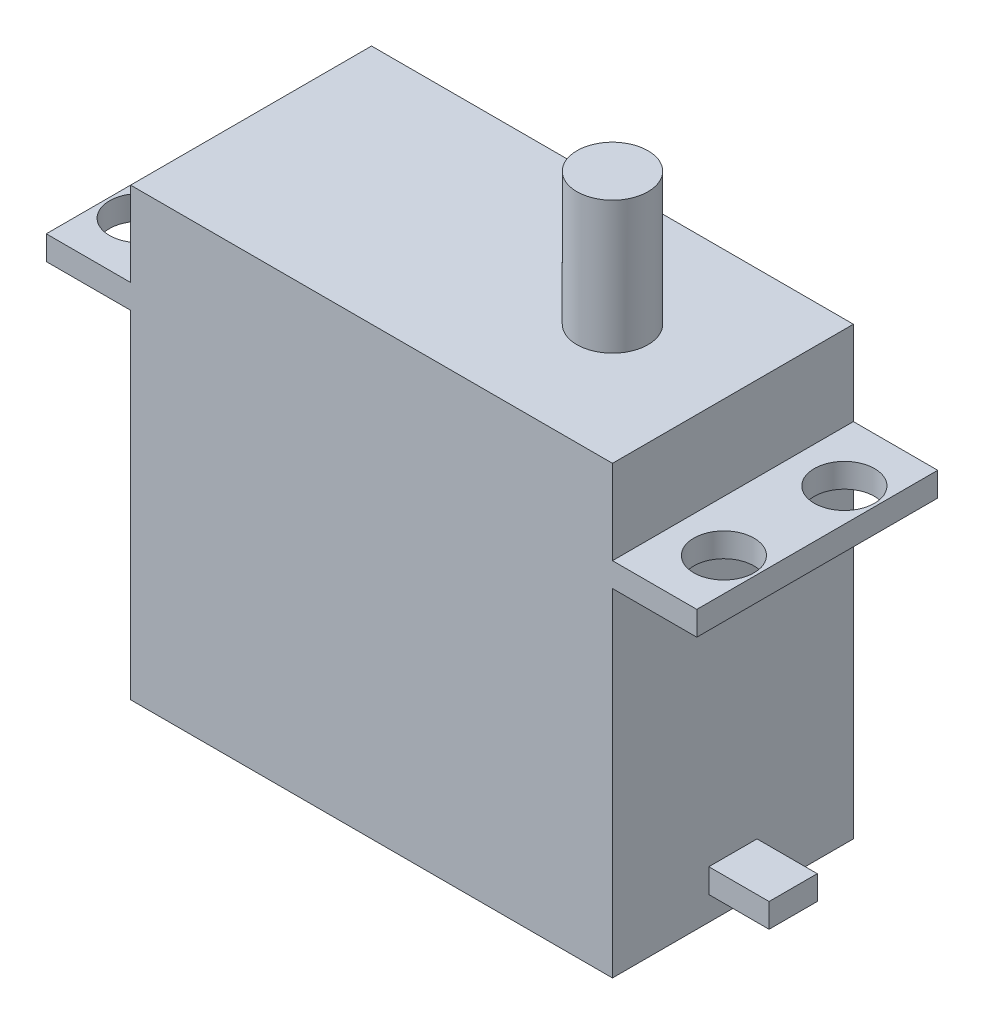
SolidWorks part; units mm, degrees
ref_plane "Front Plane" through (0, 0, 0) normal (0, 0, 1) x (1, 0, 0)
ref_plane "Top Plane" through (0, 0, 0) normal (0, 1, 0) x (1, 0, 0)
ref_plane "Right Plane" through (0, 0, 0) normal (1, 0, 0) x (0, 0, -1)
sketch "Sketch1" plane through (0, 0, 0) normal (0, 0, 1) x (1, 0, 0)
  line L0 (0, -9) -> (0, -37)
  line L1 (0, 0) -> (40, 0)
  line L2 (0, 0) -> (0, -7)
  line L3 (0, -37) -> (40, -37)
  line L4 (40, 0) -> (40, -7)
  line L5 (-7, -7) -> (0, -7)
  line L6 (-7, -7) -> (-7, -9)
  line L7 (-7, -9) -> (0, -9)
  line L9 (40, -7) -> (47, -7)
  line L11 (40, -9) -> (47, -9)
  line L12 (47, -7) -> (47, -9)
  line L13 (40, -9) -> (40, -37)
  dimension "D1" = 40
  dimension "D2" = 37
  dimension "D3" = 7
  dimension "D4" = 28
  dimension "D6" = 2
extrude "Boss-Extrude1" add sketch "Sketch1" along normal blind 20
ref_plane "Plane1" through (0, 0, 0) normal (0, 1, 0) x (1, 0, 0)
sketch "Sketch2" plane through (0, 0, 0) normal (0, 1, 0) x (1, 0, 0)
  line L0 (40, -20) -> (40, 0) construction
  line L2 (40, -20) -> (0, -20) construction
  circle A0 centre (30, -10) radius 2.95
  dimension "D3" = 5.9
  dimension "D1" = 10
  dimension "D2" = 10
extrude "Boss-Extrude2" add sketch "Sketch2" along normal blind 11
ref_plane "Plane3" through (0, -7, 0) normal (0, 1, 0) x (1, 0, 0)
sketch "Sketch4" plane through (0, -7, 0) normal (0, 1, 0) x (1, 0, 0)
  line L0 (0, 0) -> (-7, 0) construction
  line L1 (47, 0) -> (40, 0) construction
  line L2 (-7, -20) -> (-7, 0) construction
  circle A0 centre (-4.25, -5) radius 2.5
  circle A1 centre (-4.25, -15) radius 2.5
  circle A2 centre (44.25, -5) radius 2.5
  circle A3 centre (44.25, -15) radius 2.5
  dimension "D3" = 5
  dimension "D8" = 5
  dimension "D1" = 10
  dimension "D2" = 5
  dimension "D4" = 5
  dimension "D5" = 10
  dimension "D6" = 48.5
  dimension "D7" = 2.75
extrude "Cut-Extrude1" cut sketch "Sketch4" against normal blind 3
ref_plane "Plane4" through (40, 0, 0) normal (1, 0, 0) x (0, 0, -1)
sketch "Sketch5" plane through (40, 0, 0) normal (1, 0, 0) x (0, 0, -1)
  line L0 (-20, -37) -> (0, -37) construction
  line L1 (-12, -33) -> (-8, -33)
  line L2 (-12, -33) -> (-12, -35)
  line L3 (-12, -35) -> (-8, -35)
  line L4 (-8, -33) -> (-8, -35)
  line L5 (0, -37) -> (0, -9) construction
  point P4 (-10, -35)
  dimension "D1" = 2
  dimension "D2" = 8
  dimension "D3" = 4
  dimension "D4" = 2
extrude "Boss-Extrude3" add sketch "Sketch5" along normal blind 5
